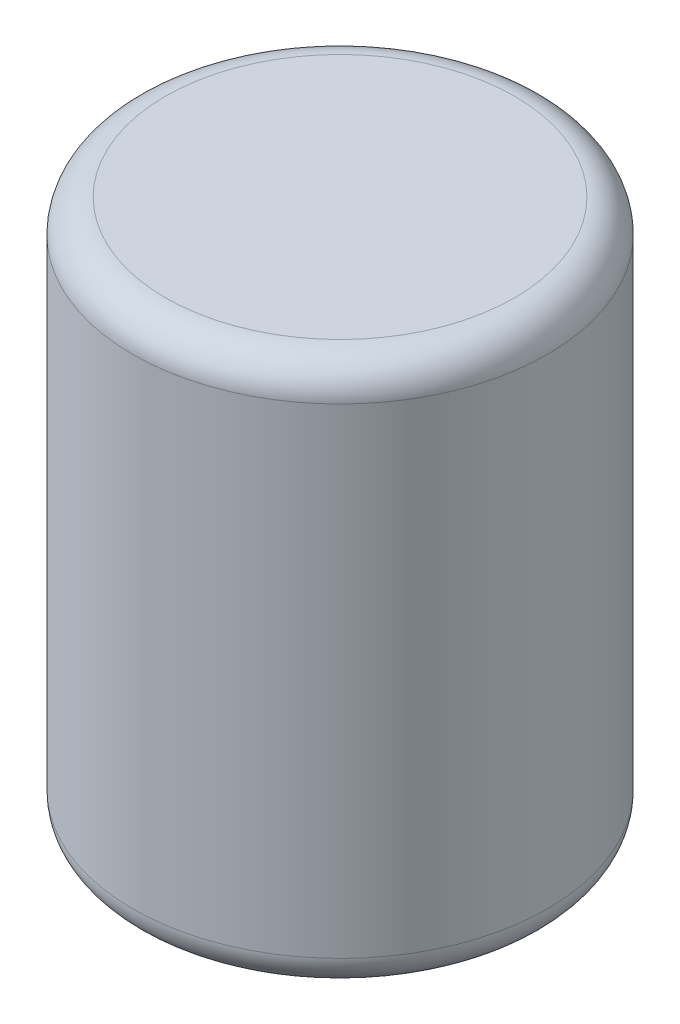
SolidWorks part; units mm, degrees
ref_plane "Спереди" through (0, 0, 0) normal (0, 0, 1) x (1, 0, 0)
ref_plane "Сверху" through (0, 0, 0) normal (0, 1, 0) x (1, 0, 0)
ref_plane "Справа" through (0, 0, 0) normal (1, 0, 0) x (0, 0, -1)
sketch "Эскиз1" plane through (0, 0, 0) normal (0, 1, 0) x (1, 0, 0)
  circle A0 centre (0, 0) radius 9.5
  dimension "D1" = 19
extrude "Бобышка-Вытянуть1" add sketch "Эскиз1" along normal blind 25
fillet "Скругление1" radius 1.5 2 edges at (0, 0, 9.5) (0, 25, 9.5)
